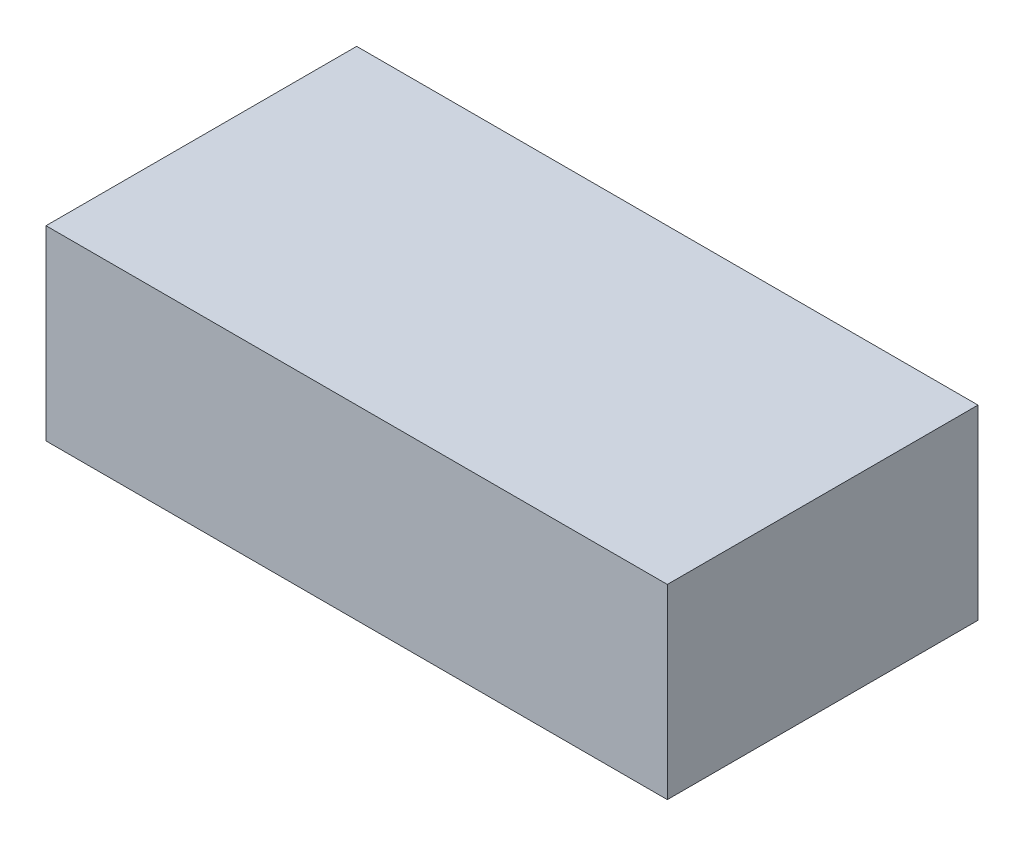
SolidWorks part; units mm, degrees
ref_plane "Front Plane" through (0, 0, 0) normal (0, 0, 1) x (1, 0, 0)
ref_plane "Top Plane" through (0, 0, 0) normal (0, 1, 0) x (1, 0, 0)
ref_plane "Right Plane" through (0, 0, 0) normal (1, 0, 0) x (0, 0, -1)
sketch "Sketch2" plane through (0, 0, 0) normal (0, 0, 1) x (1, 0, 0)
  line L1 (-10, -3) -> (10, -3)
  line L2 (-10, -3) -> (-10, 3)
  line L3 (-10, 3) -> (10, 3)
  line L4 (10, -3) -> (10, 3)
  line L5 (-10, -3) -> (10, 3) construction
  line L6 (-10, 3) -> (10, -3) construction
  point P0 (0, 0)
  point P6 (0, 0)
  dimension "D1" = 20
  dimension "D2" = 6
extrude "Boss-Extrude1" add sketch "Sketch2" along normal blind 10
